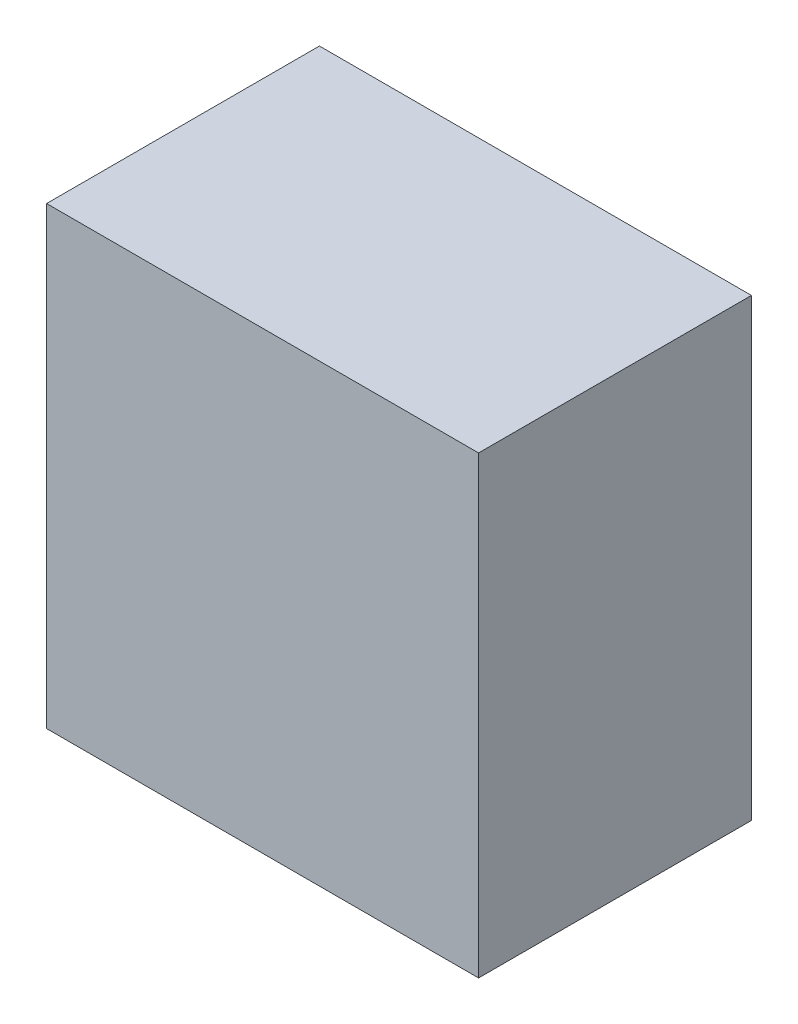
SolidWorks part; units mm, degrees
material "Nickel"
ref_plane "Front Plane" through (0, 0, 0) normal (0, 0, 1) x (1, 0, 0)
ref_plane "Top Plane" through (0, 0, 0) normal (0, 1, 0) x (1, 0, 0)
ref_plane "Right Plane" through (0, 0, 0) normal (1, 0, 0) x (0, 0, -1)
sketch "Sketch1" plane through (0, 0, 0) normal (0, 1, 0) x (1, 0, 0)
  line L1 (0, 0) -> (723.9, 0)
  line L2 (0, 0) -> (0, 457.2)
  line L3 (0, 457.2) -> (723.9, 457.2)
  line L4 (723.9, 0) -> (723.9, 457.2)
  dimension "D1" = 723.9
  dimension "D2" = 457.2
extrude "Extrude1" add sketch "Sketch1" along normal blind 762
